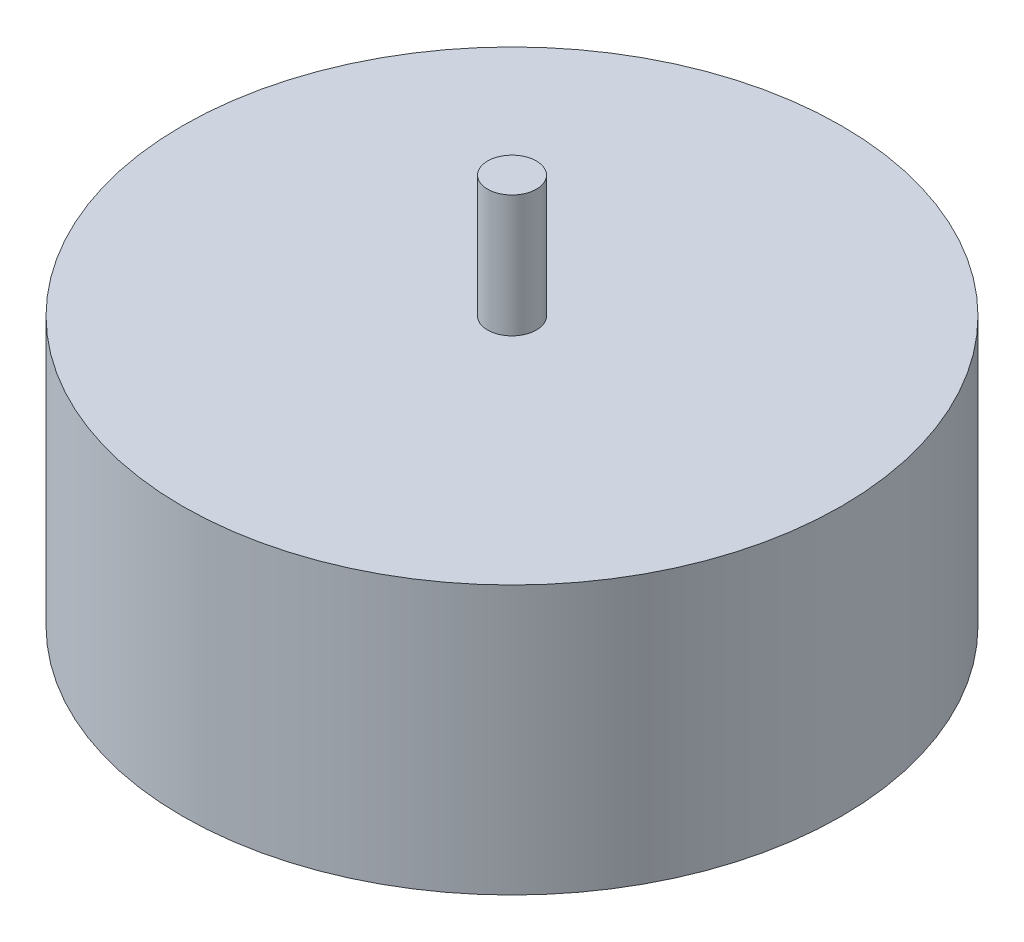
SolidWorks part; units mm, degrees
ref_plane "Front Plane" through (0, 0, 0) normal (0, 0, 1) x (1, 0, 0)
ref_plane "Top Plane" through (0, 0, 0) normal (0, 1, 0) x (1, 0, 0)
ref_plane "Right Plane" through (0, 0, 0) normal (1, 0, 0) x (0, 0, -1)
sketch "Sketch1" plane through (0, 0, 0) normal (0, 1, 0) x (1, 0, 0)
  circle A0 centre (0, 0) radius 27
  dimension "D1" = 54
extrude "Boss-Extrude1" add sketch "Sketch1" along normal blind 22
sketch "Sketch2" plane through (0, 22, 0) normal (0, 1, 0) x (1, 0, 0)
  circle A0 centre (0, 0) radius 2
  dimension "D1" = 4
extrude "Boss-Extrude2" add sketch "Sketch2" along normal blind 10 and the other way blind 30.48
